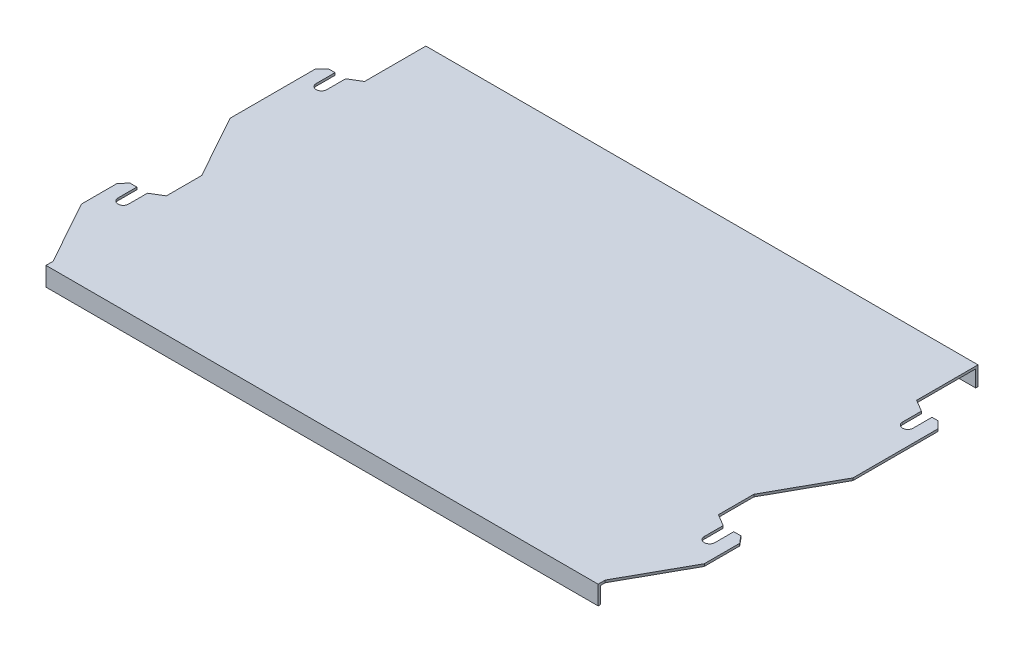
SolidWorks part; units mm, degrees
ref_plane "Front Plane" through (0, 0, 0) normal (0, 0, 1) x (1, 0, 0)
ref_plane "Top Plane" through (0, 0, 0) normal (0, 1, 0) x (1, 0, 0)
ref_plane "Right Plane" through (0, 0, 0) normal (1, 0, 0) x (0, 0, -1)
sketch "Sketch1" plane through (0, 0, 0) normal (1, 0, 0) x (0, 0, -1)
  line L0 (-80.5, -8) -> (-80.5, 0)
  line L1 (-80.5, 0) -> (80.5, 0)
  line L2 (80.5, 0) -> (80.5, -8)
  point P6 (0, 0)
  dimension "D1" = 161
  dimension "D2" = 8
extrude "Extrude-Thin1" add sketch "Sketch1" along normal mid plane 264 thin
sketch "Sketch2" plane through (0, 0, 0) normal (0, 1, 0) x (1, 0, 0)
  line L0 (-117, 80.5) -> (-117, 54.5)
  line L1 (132, 80.5) -> (-132, 80.5) construction
  line L2 (-117, 54.5) -> (-122, 51.5)
  line L3 (-122, 51.5) -> (-122, 43.5)
  line L4 (-117, -77.5) -> (-117, -80.5)
  line L5 (-126.5, 43.5) -> (-126.5, 51.5)
  line L6 (-126.5, 51.5) -> (-129, 51.5)
  line L7 (-129, 51.5) -> (-132, 48.5)
  line L8 (-132, -80.5) -> (-132, 80.5) construction
  line L9 (-132, 48.5) -> (-132, 12.5)
  line L10 (-132, 12.5) -> (-117, -14.5)
  line L11 (-117, -14.5) -> (-117, -29.5)
  line L12 (-117, -29.5) -> (-122, -32.5)
  line L13 (-122, -32.5) -> (-122, -40.5)
  line L14 (132, -80.5) -> (-132, -80.5) construction
  line L15 (-126.5, -40.5) -> (-126.5, -32.5)
  line L16 (-126.5, -32.5) -> (-129.5, -32.5)
  line L17 (-129.5, -32.5) -> (-132, -35.5)
  line L18 (-132, -35.5) -> (-132, -50.5)
  line L19 (-132, -50.5) -> (-117, -77.5)
  line L20 (-111.3765, 41.25) -> (-135.7102, 41.25) construction
  line L21 (-117, -80.5) -> (-140, -80.5)
  line L22 (-140, -80.5) -> (-140, 80.5)
  line L23 (-140, 80.5) -> (-117, 80.5)
  line L24 (-114.8861, -42.75) -> (-135.7102, -42.75) construction
  arc A0 (-126.5, -40.5) -> (-122, -40.5) centre (-124.25, -40.5) ccw
  arc A1 (-126.5, 43.5) -> (-122, 43.5) centre (-124.25, 43.5) ccw
  point P31 (-127.5, 51.5)
  point P34 (-128.8485, 51.5)
  dimension "D1" = 26
  dimension "D2" = 15
  dimension "D3" = 3
  dimension "D4" = 3
  dimension "D5" = 84
  dimension "D6" = 8
  dimension "D7" = 3
  dimension "D8" = 122
  dimension "D9" = 3
  dimension "D10" = 3
  dimension "D11" = 3
  dimension "D12" = 27
  dimension "D13" = 15
  dimension "D14" = 8
  dimension "D15" = 126.5
  dimension "D16" = 3
extrude "Cut-Extrude1" cut sketch "Sketch2" against normal blind 10
mirror "Mirror1" about plane through (0, 0, 0) normal (1, 0, 0) of "Cut-Extrude1"
